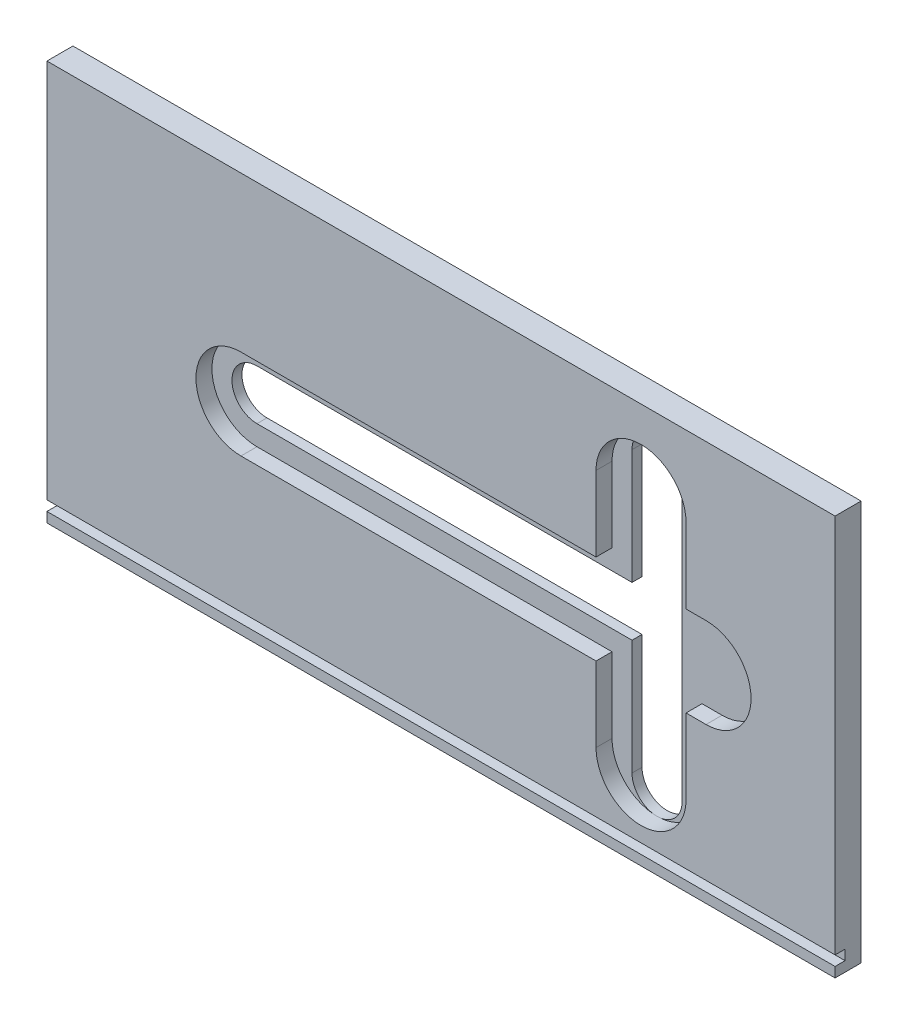
SolidWorks part; units mm, degrees
ref_plane "正面" through (0, 0, 0) normal (0, 0, 1) x (1, 0, 0)
ref_plane "平面" through (0, 0, 0) normal (0, 1, 0) x (1, 0, 0)
ref_plane "右側面" through (0, 0, 0) normal (1, 0, 0) x (0, 0, -1)
sketch "ｽｹｯﾁ1" plane through (0, 0, 0) normal (0, 0, 1) x (1, 0, 0)
  line L1 (-69.2801, 161.5071) -> (324.7199, 161.5071)
  line L2 (-69.2801, 161.5071) -> (-69.2801, -38.4929)
  line L3 (-69.2801, -38.4929) -> (324.7199, -38.4929)
  line L4 (324.7199, 161.5071) -> (324.7199, -38.4929)
  dimension "D1" = 394
  dimension "D3" = 200
extrude "ﾎﾞｽ - 押し出し1" add sketch "ｽｹｯﾁ1" along normal blind 13
sketch "ｽｹｯﾁ2" plane through (0, 0, 13) normal (0, 0, 1) x (1, 0, 0)
  line L0 (324.7199, -38.4929) -> (324.7199, 161.5071) construction
  line L1 (324.7199, -33.4929) -> (-69.2801, -33.4929)
  line L2 (324.7199, -33.4929) -> (324.7199, -28.4929)
  line L3 (324.7199, -28.4929) -> (-69.2801, -28.4929)
  line L4 (-69.2801, -33.4929) -> (-69.2801, -28.4929)
  line L5 (-69.2801, 161.5071) -> (-69.2801, -38.4929) construction
  line L7 (-69.2801, -38.4929) -> (324.7199, -38.4929) construction
  dimension "D1" = 5
  dimension "D2" = 394
  dimension "D3" = 5
extrude "ｶｯﾄ - 押し出し1" cut sketch "ｽｹｯﾁ2" against normal blind 5
sketch "ｽｹｯﾁ3" plane through (0, 0, 13) normal (0, 0, 1) x (1, 0, 0)
  line L0 (27.7199, 61.5071) -> (-69.2801, 61.5071) construction
  line L1 (27.7199, 74.0071) -> (215.2199, 74.0071)
  line L2 (-69.2801, 161.5071) -> (-69.2801, -28.4929) construction
  line L3 (27.7199, 49.0071) -> (215.2199, 49.0071)
  line L4 (215.2199, 131.5071) -> (215.2199, 74.0071)
  line L6 (227.7199, -8.4929) -> (324.7199, -8.4929) construction
  line L8 (96.6525, 74.0071) -> (96.6525, 161.5071) construction
  line L9 (324.7199, 161.5071) -> (-69.2801, 161.5071) construction
  line L10 (111.609, 49.0071) -> (111.609, -38.4929) construction
  line L11 (-69.2801, -38.4929) -> (324.7199, -38.4929) construction
  line L12 (215.2199, 49.0071) -> (215.2199, -8.4929)
  line L13 (324.7199, -28.4929) -> (324.7199, 161.5071) construction
  line L16 (240.2199, 131.5071) -> (240.2199, -8.4929)
  arc A0 (215.2199, 131.5071) -> (240.2199, 131.5071) centre (227.7199, 131.5071) cw
  arc A1 (27.7199, 49.0071) -> (27.7199, 74.0071) centre (27.7199, 61.5071) cw
  arc A2 (215.2199, -8.4929) -> (240.2199, -8.4929) centre (227.7199, -8.4929) ccw
  dimension "D1" = 200
  dimension "D3" = 25
  dimension "D5" = 25
extrude "ｶｯﾄ - 押し出し2" cut sketch "ｽｹｯﾁ3" against normal through all
sketch "ｽｹｯﾁ6" plane through (0, 0, 13) normal (0, 0, 1) x (1, 0, 0)
  line L0 (324.7199, 161.5071) -> (-69.2801, 161.5071) construction
  line L1 (27.7199, 84.0071) -> (205.2199, 84.0071)
  line L2 (27.7199, 39.0071) -> (205.2199, 39.0071)
  line L3 (205.2199, 121.5071) -> (205.2199, 84.0071)
  line L4 (-69.2801, -38.4929) -> (324.7199, -38.4929) construction
  line L5 (95.8401, 84.0071) -> (95.8401, 161.5071) construction
  line L6 (110.7965, 39.0071) -> (110.7965, -38.4929) construction
  line L7 (205.2199, 39.0071) -> (205.2199, 1.5071)
  line L8 (250.2199, 1.5071) -> (250.2199, 39.0071)
  line L9 (27.7199, 61.5071) -> (-69.2801, 61.5071) construction
  line L10 (-69.2801, 161.5071) -> (-69.2801, -28.4929) construction
  line L11 (227.7199, -13.6641) -> (324.7199, -13.6641) construction
  line L12 (324.7199, -28.4929) -> (324.7199, 161.5071) construction
  line L13 (250.2199, 84.0071) -> (260.2199, 84.0071)
  line L14 (250.2199, 39.0071) -> (260.2199, 39.0071)
  line L15 (215.2199, 49.0071) -> (215.2199, -8.4929) construction
  line L16 (250.2199, 84.0071) -> (250.2199, 121.5071)
  arc A0 (27.7199, 84.0071) -> (27.7199, 39.0071) centre (27.7199, 61.5071) ccw
  arc A1 (27.7199, 74.0071) -> (27.7199, 49.0071) centre (27.7199, 61.5071) ccw construction
  arc A2 (205.2199, 121.5071) -> (250.2199, 121.5071) centre (227.7199, 121.5071) cw
  arc A3 (205.2199, 1.5071) -> (250.2199, 1.5071) centre (227.7199, 1.5071) ccw
  arc A4 (240.2199, 131.5071) -> (215.2199, 131.5071) centre (227.7199, 131.5071) ccw construction
  arc A5 (260.2199, 84.0071) -> (260.2199, 39.0071) centre (260.2199, 61.5071) cw
  dimension "D4" = 10
  dimension "D6" = 0
  dimension "D7" = 10
  dimension "D1" = 10
  dimension "D2" = 45
  dimension "D3" = 200
extrude "ｶｯﾄ - 押し出し3" cut sketch "ｽｹｯﾁ6" against normal blind 8
